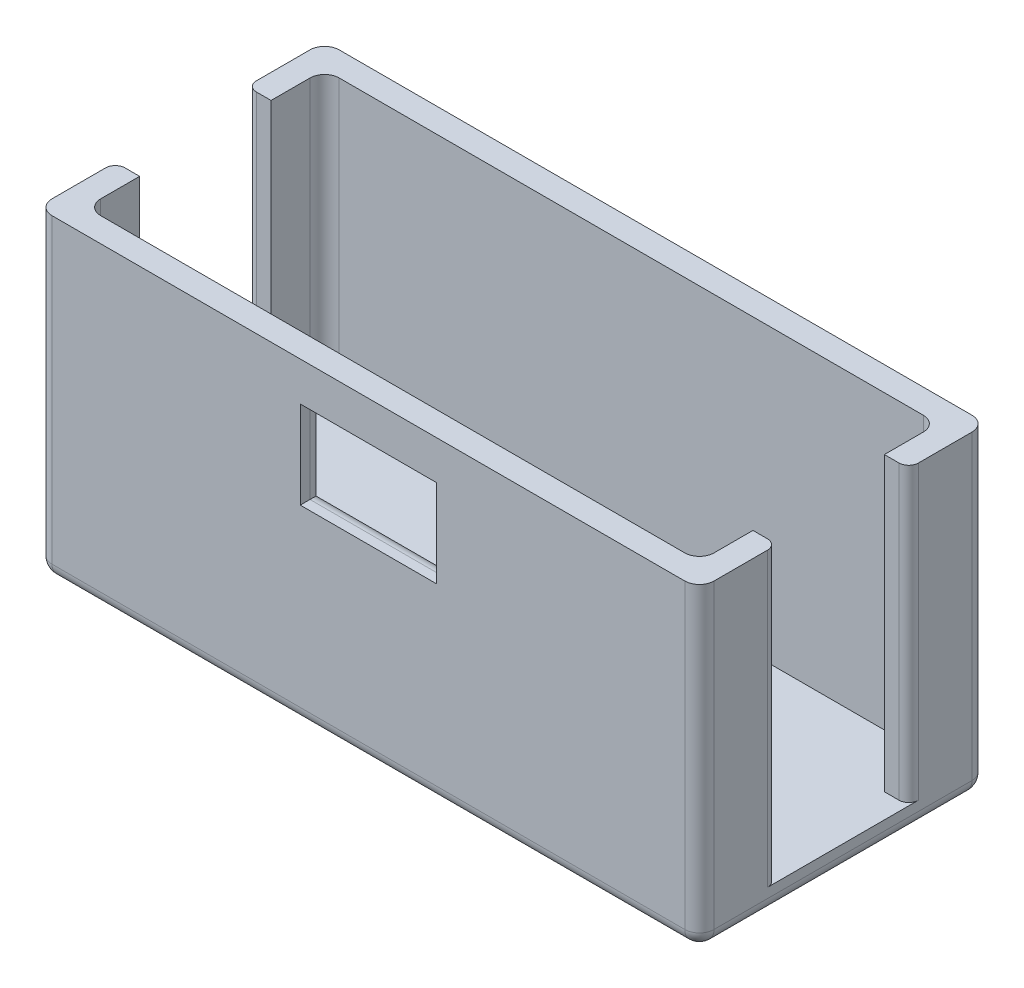
SolidWorks part; units mm, degrees
ref_plane "Front Plane" through (0, 0, 0) normal (0, 0, 1) x (1, 0, 0)
ref_plane "Top Plane" through (0, 0, 0) normal (0, 1, 0) x (1, 0, 0)
ref_plane "Right Plane" through (0, 0, 0) normal (1, 0, 0) x (0, 0, -1)
sketch "Sketch1" plane through (0, 0, 0) normal (0, 1, 0) x (1, 0, 0)
  line L0 (-34, -14.75) -> (-34, 14.75)
  line L1 (-31.5, -12.25) -> (31.5, -12.25)
  line L2 (-31.5, -12.25) -> (-31.5, 12.25)
  line L3 (-31.5, 12.25) -> (31.5, 12.25)
  line L4 (31.5, -12.25) -> (31.5, 12.25)
  line L5 (-31.5, -12.25) -> (31.5, 12.25) construction
  line L6 (-31.5, 12.25) -> (31.5, -12.25) construction
  line L7 (-34, 14.75) -> (34, 14.75)
  line L8 (34, -14.75) -> (34, 14.75)
  line L9 (-34, -14.75) -> (34, -14.75)
  point P0 (0, 0)
  dimension "D1" = 63
  dimension "D2" = 24.5
  dimension "D3" = 2.5
extrude "Boss-Extrude1" add sketch "Sketch1" along normal blind 2.5 contours L0 L9 L8 L7 L4 L1 L2 L3
sketch "Sketch2" plane through (0, 2.5, 0) normal (0, 1, 0) x (1, 0, 0)
  line L0 (0, 0) -> (-3.4182, 0)
  line L1 (-1.375, 0) -> (1.375, 0) construction
  line L2 (-3.4182, 0) -> (0, 0)
  line L3 (0, 0) -> (0, 2.5513)
  line L4 (0, -1.375) -> (0, 1.375) construction
  line L5 (-34, 14.75) -> (-34, 6.75)
  line L6 (-34, -14.75) -> (-34, 14.75) construction
  line L7 (-34, 6.75) -> (-31.5, 6.75)
  line L8 (-31.5, 6.75) -> (-31.5, 12.25)
  line L9 (-31.5, 12.25) -> (31.5, 12.25)
  line L10 (0, 12.25) -> (0, 14.75)
  line L11 (34, 14.75) -> (-34, 14.75)
  line L12 (0, -12.25) -> (0, -14.75)
  line L13 (-31.5, -12.25) -> (31.5, -12.25)
  line L14 (-31.5, -6.75) -> (-31.5, -12.25)
  line L15 (-34, -6.75) -> (-31.5, -6.75)
  line L16 (-34, -14.75) -> (-34, -6.75)
  line L17 (34, -14.75) -> (-34, -14.75)
  line L18 (31.5, 6.75) -> (31.5, 12.25)
  line L19 (34, 6.75) -> (31.5, 6.75)
  line L20 (34, 14.75) -> (34, 6.75)
  line L21 (31.5, -6.75) -> (31.5, -12.25)
  line L22 (34, -6.75) -> (31.5, -6.75)
  line L23 (34, -14.75) -> (34, -6.75)
  point P13 (-31.5, 9.5)
  line M15 (-34, 14.75) -> (-34, -14.75)
  line M16 (-34, -14.75) -> (34, -14.75)
  line M17 (34, -14.75) -> (34, 14.75)
  line M18 (34, 14.75) -> (-34, 14.75)
  dimension "D1" = 2.5
  dimension "D2" = 2.5
  dimension "D3" = 5.5
extrude "Boss-Extrude2" add sketch "Sketch2" along normal blind 30 contours L15 L12 L13 L14 M15 M16 | L22 L21 L13 L12 M17 M16 | L19 L10 L9 L18 M17 M18 | L9 L10 L7 L8 M18 M15
sketch "Sketch3" plane through (0, 0, -12.25) normal (0, 0, 1) x (1, 0, 0)
  line L0 (0, 32.5) -> (0, 28.5)
  line L1 (-34, 32.5) -> (34, 32.5) construction
  line L2 (0, -16.225) -> (0, 16.225) construction
  line L3 (0, 28.5) -> (-7, 28.5)
  line L4 (-7, 28.5) -> (-7, 19.5)
  line L5 (-7, 19.5) -> (7, 19.5)
  line L6 (7, 19.5) -> (7, 28.5)
  line L7 (7, 28.5) -> (0, 28.5)
  dimension "D1" = 4
  dimension "D2" = 14
  dimension "D3" = 7
  dimension "D4" = 9
extrude "Cut-Extrude1" cut sketch "Sketch3" along normal blind 50.5 contours L6 L7 L3 L4 L5
fillet "Fillet1" radius 1.5 16 edges at (0, 0, 14.75) (34, 0, 0) (0, 0, -14.75) (-34, 0, 0) (31.5, 17.5, -12.25) (-7, 24, 12.25) (0, 28.5, 12.25) (7, 24, 12.25) (0, 19.5, 12.25) (-34, 16.25, -14.75) (34, 16.25, -14.75) (34, 16.25, 14.75) (-34, 16.25, 14.75) (31.5, 17.5, 12.25) (-31.5, 17.5, 12.25) (-31.5, 17.5, -12.25)
fillet "Fillet2" radius 1 4 edges at (-34, 17.5, 6.75) (-34, 17.5, -6.75) (34, 17.5, 6.75) (34, 17.5, -6.75)
